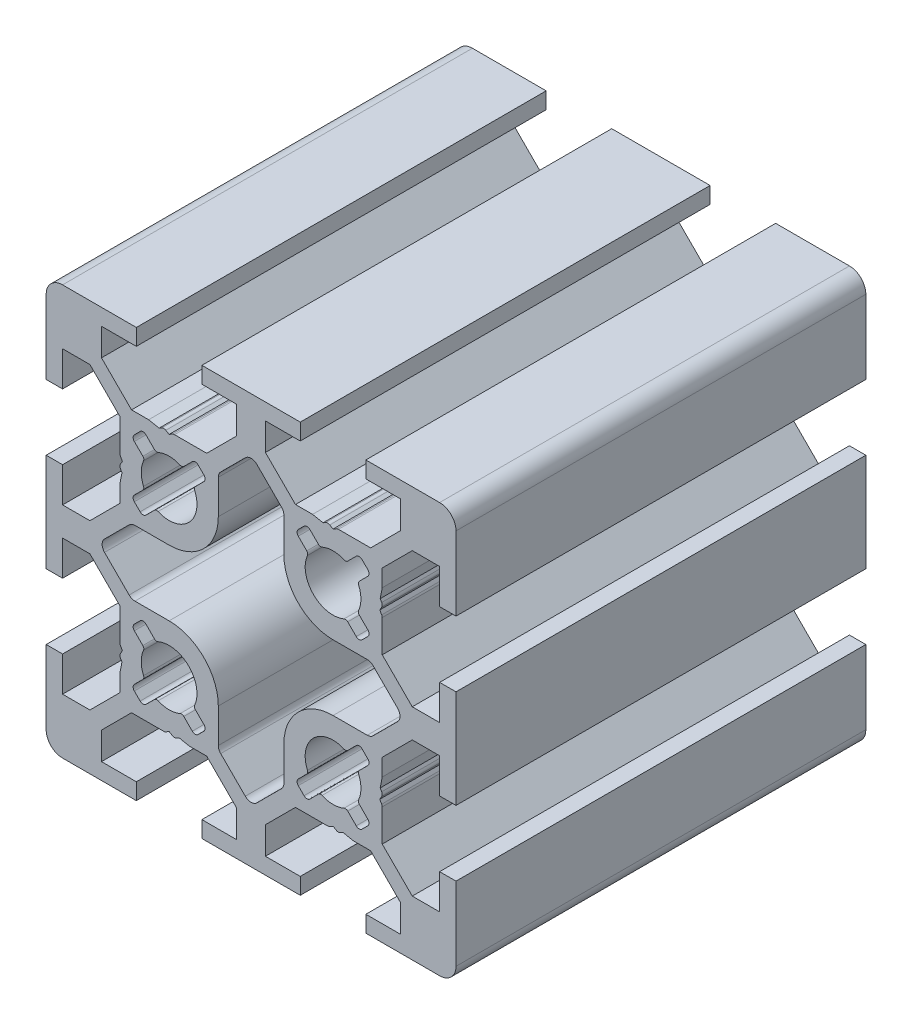
SolidWorks part; units mm, degrees
ref_plane "Front Plane" through (0, 0, 0) normal (0, 0, 1) x (1, 0, 0)
ref_plane "Top Plane" through (0, 0, 0) normal (0, 1, 0) x (1, 0, 0)
ref_plane "Right Plane" through (0, 0, 0) normal (1, 0, 0) x (0, 0, -1)
ref_plane "Plane1" through (0, 0, 0) normal (0, 0, 1) x (1, 0, 0)
sketch "Sketch1" plane through (0, 0, 0) normal (0, 0, 1) x (1, 0, 0)
  line L0 (-25, 23) -> (-25, 14)
  line L1 (-25, 14) -> (-23, 14)
  line L2 (-23, 14) -> (-23, 18.25)
  line L3 (-23, 18.25) -> (-19.6642, 18.25)
  line L4 (-19.6642, 18.25) -> (-16, 14.5858)
  line L5 (-16, 14.5858) -> (-16, 10.6536)
  line L6 (-15.933, 10.4036) -> (-15.7, 10)
  line L7 (-15.7, 10) -> (-15.933, 9.5964)
  line L8 (-15.933, 9.0964) -> (-15.751, 8.7811)
  line L9 (-15.751, 8.7811) -> (-16, 7.5)
  line L10 (-16, 7.5) -> (-16, 5.4142)
  line L11 (-16, 5.4142) -> (-19.6642, 1.75)
  line L12 (-19.6642, 1.75) -> (-23, 1.75)
  line L13 (-23, 1.75) -> (-23, 6)
  line L14 (-23, 6) -> (-25, 6)
  line L15 (-25, 6) -> (-25, -6)
  line L16 (-25, -6) -> (-23, -6)
  line L17 (-23, -6) -> (-23, -1.75)
  line L18 (-23, -1.75) -> (-19.6642, -1.75)
  line L19 (-19.6642, -1.75) -> (-16, -5.4142)
  line L20 (-16, -5.4142) -> (-16, -9.3464)
  line L21 (-15.933, -9.5964) -> (-15.7, -10)
  line L22 (-15.7, -10) -> (-15.933, -10.4036)
  line L23 (-15.933, -10.9036) -> (-15.751, -11.2189)
  line L24 (-15.751, -11.2189) -> (-16, -12.5)
  line L25 (-16, -12.5) -> (-16, -14.5858)
  line L26 (-16, -14.5858) -> (-19.6642, -18.25)
  line L27 (-19.6642, -18.25) -> (-23, -18.25)
  line L28 (-23, -18.25) -> (-23, -14)
  line L29 (-23, -14) -> (-25, -14)
  line L30 (-25, -14) -> (-25, -23)
  line L31 (-23, -25) -> (-14, -25)
  line L32 (-14, -25) -> (-14, -23)
  line L33 (-14, -23) -> (-18.25, -23)
  line L34 (-18.25, -23) -> (-18.25, -19.6642)
  line L35 (-18.25, -19.6642) -> (-14.5858, -16)
  line L36 (-14.5858, -16) -> (-10.6536, -16)
  line L37 (-10.4036, -15.933) -> (-10, -15.7)
  line L38 (-10, -15.7) -> (-9.5964, -15.933)
  line L39 (-9.0964, -15.933) -> (-8.7811, -15.751)
  line L40 (-8.7811, -15.751) -> (-7.5, -16)
  line L41 (-7.5, -16) -> (-5.4142, -16)
  line L42 (-5.4142, -16) -> (-1.75, -19.6642)
  line L43 (-1.75, -19.6642) -> (-1.75, -23)
  line L44 (-1.75, -23) -> (-6, -23)
  line L45 (-6, -23) -> (-6, -25)
  line L46 (-6, -25) -> (6, -25)
  line L47 (6, -25) -> (6, -23)
  line L48 (6, -23) -> (1.75, -23)
  line L49 (1.75, -23) -> (1.75, -19.6642)
  line L50 (1.75, -19.6642) -> (5.4142, -16)
  line L51 (5.4142, -16) -> (9.3464, -16)
  line L52 (9.5964, -15.933) -> (10, -15.7)
  line L53 (10, -15.7) -> (10.4036, -15.933)
  line L54 (10.9036, -15.933) -> (11.2189, -15.751)
  line L55 (11.2189, -15.751) -> (12.5, -16)
  line L56 (12.5, -16) -> (14.5858, -16)
  line L57 (14.5858, -16) -> (18.25, -19.6642)
  line L58 (18.25, -19.6642) -> (18.25, -23)
  line L59 (18.25, -23) -> (14, -23)
  line L60 (14, -23) -> (14, -25)
  line L61 (14, -25) -> (23, -25)
  line L62 (25, -23) -> (25, -14)
  line L63 (25, -14) -> (23, -14)
  line L64 (23, -14) -> (23, -18.25)
  line L65 (23, -18.25) -> (19.6642, -18.25)
  line L66 (19.6642, -18.25) -> (16, -14.5858)
  line L67 (16, -14.5858) -> (16, -10.6536)
  line L68 (15.933, -10.4036) -> (15.7, -10)
  line L69 (15.7, -10) -> (15.933, -9.5964)
  line L70 (15.933, -9.0964) -> (15.751, -8.7811)
  line L71 (15.751, -8.7811) -> (16, -7.5)
  line L72 (16, -7.5) -> (16, -5.4142)
  line L73 (16, -5.4142) -> (19.6642, -1.75)
  line L74 (19.6642, -1.75) -> (23, -1.75)
  line L75 (23, -1.75) -> (23, -6)
  line L76 (23, -6) -> (25, -6)
  line L77 (25, -6) -> (25, 6)
  line L78 (25, 6) -> (23, 6)
  line L79 (23, 6) -> (23, 1.75)
  line L80 (23, 1.75) -> (19.6642, 1.75)
  line L81 (19.6642, 1.75) -> (16, 5.4142)
  line L82 (16, 5.4142) -> (16, 9.3464)
  line L83 (15.933, 9.5964) -> (15.7, 10)
  line L84 (15.7, 10) -> (15.933, 10.4036)
  line L85 (15.933, 10.9036) -> (15.751, 11.2189)
  line L86 (15.751, 11.2189) -> (16, 12.5)
  line L87 (16, 12.5) -> (16, 14.5858)
  line L88 (16, 14.5858) -> (19.6642, 18.25)
  line L89 (19.6642, 18.25) -> (23, 18.25)
  line L90 (23, 18.25) -> (23, 14)
  line L91 (23, 14) -> (25, 14)
  line L92 (25, 14) -> (25, 23)
  line L93 (23, 25) -> (14, 25)
  line L94 (14, 25) -> (14, 23)
  line L95 (14, 23) -> (18.25, 23)
  line L96 (18.25, 23) -> (18.25, 19.6642)
  line L97 (18.25, 19.6642) -> (14.5858, 16)
  line L98 (14.5858, 16) -> (10.6536, 16)
  line L99 (10.4036, 15.933) -> (10, 15.7)
  line L100 (10, 15.7) -> (9.5964, 15.933)
  line L101 (9.0964, 15.933) -> (8.7811, 15.751)
  line L102 (8.7811, 15.751) -> (7.5, 16)
  line L103 (7.5, 16) -> (5.4142, 16)
  line L104 (5.4142, 16) -> (1.75, 19.6642)
  line L105 (1.75, 19.6642) -> (1.75, 23)
  line L106 (1.75, 23) -> (6, 23)
  line L107 (6, 23) -> (6, 25)
  line L108 (6, 25) -> (-6, 25)
  line L109 (-6, 25) -> (-6, 23)
  line L110 (-6, 23) -> (-1.75, 23)
  line L111 (-1.75, 23) -> (-1.75, 19.6642)
  line L112 (-1.75, 19.6642) -> (-5.4142, 16)
  line L113 (-5.4142, 16) -> (-9.3464, 16)
  line L114 (-9.5964, 15.933) -> (-10, 15.7)
  line L115 (-10, 15.7) -> (-10.4036, 15.933)
  line L116 (-10.9036, 15.933) -> (-11.2189, 15.751)
  line L117 (-11.2189, 15.751) -> (-12.5, 16)
  line L118 (-12.5, 16) -> (-14.5858, 16)
  line L119 (-14.5858, 16) -> (-18.25, 19.6642)
  line L120 (-18.25, 19.6642) -> (-18.25, 23)
  line L121 (-18.25, 23) -> (-14, 23)
  line L122 (-14, 23) -> (-14, 25)
  line L123 (-14, 25) -> (-23, 25)
  line L124 (-17.8787, -0.7071) -> (-14.8787, -3.7071)
  line L125 (-14.1716, -4) -> (-10, -4)
  line L126 (-4, -10) -> (-4, -14.1716)
  line L127 (-3.7071, -14.8787) -> (-0.7071, -17.8787)
  line L128 (0.7071, -17.8787) -> (3.7071, -14.8787)
  line L129 (4, -14.1716) -> (4, -10)
  line L130 (10, -4) -> (14.1716, -4)
  line L131 (14.8787, -3.7071) -> (17.8787, -0.7071)
  line L132 (17.8787, 0.7071) -> (14.8787, 3.7071)
  line L133 (14.1716, 4) -> (10, 4)
  line L134 (4, 10) -> (4, 14.1716)
  line L135 (3.7071, 14.8787) -> (0.7071, 17.8787)
  line L136 (-0.7071, 17.8787) -> (-3.7071, 14.8787)
  line L137 (-4, 14.1716) -> (-4, 10)
  line L138 (-10, 4) -> (-14.1716, 4)
  line L139 (-14.8787, 3.7071) -> (-17.8787, 0.7071)
  arc A0 (-16, 10.6536) -> (-15.933, 10.4036) centre (-15.5, 10.6536) ccw
  arc A1 (-15.933, 9.5964) -> (-15.933, 9.0964) centre (-15.5, 9.3464) ccw
  arc A2 (-16, -9.3464) -> (-15.933, -9.5964) centre (-15.5, -9.3464) ccw
  arc A3 (-15.933, -10.4036) -> (-15.933, -10.9036) centre (-15.5, -10.6536) ccw
  arc A4 (-25, -23) -> (-23, -25) centre (-23, -23) ccw
  arc A5 (-10.6536, -16) -> (-10.4036, -15.933) centre (-10.6536, -15.5) ccw
  arc A6 (-9.5964, -15.933) -> (-9.0964, -15.933) centre (-9.3464, -15.5) ccw
  arc A7 (9.3464, -16) -> (9.5964, -15.933) centre (9.3464, -15.5) ccw
  arc A8 (10.4036, -15.933) -> (10.9036, -15.933) centre (10.6536, -15.5) ccw
  arc A9 (23, -25) -> (25, -23) centre (23, -23) ccw
  arc A10 (16, -10.6536) -> (15.933, -10.4036) centre (15.5, -10.6536) ccw
  arc A11 (15.933, -9.5964) -> (15.933, -9.0964) centre (15.5, -9.3464) ccw
  arc A12 (16, 9.3464) -> (15.933, 9.5964) centre (15.5, 9.3464) ccw
  arc A13 (15.933, 10.4036) -> (15.933, 10.9036) centre (15.5, 10.6536) ccw
  arc A14 (25, 23) -> (23, 25) centre (23, 23) ccw
  arc A15 (10.6536, 16) -> (10.4036, 15.933) centre (10.6536, 15.5) ccw
  arc A16 (9.5964, 15.933) -> (9.0964, 15.933) centre (9.3464, 15.5) ccw
  arc A17 (-9.3464, 16) -> (-9.5964, 15.933) centre (-9.3464, 15.5) ccw
  arc A18 (-10.4036, 15.933) -> (-10.9036, 15.933) centre (-10.6536, 15.5) ccw
  arc A19 (-23, 25) -> (-25, 23) centre (-23, 23) ccw
  arc A20 (-17.8787, 0.7071) -> (-17.8787, -0.7071) centre (-17.1716, 0) ccw
  arc A21 (-14.8787, -3.7071) -> (-14.1716, -4) centre (-14.1716, -3) ccw
  arc A22 (-10, -4) -> (-4, -10) centre (-10, -10) cw
  arc A23 (-4, -14.1716) -> (-3.7071, -14.8787) centre (-3, -14.1716) ccw
  arc A24 (-0.7071, -17.8787) -> (0.7071, -17.8787) centre (0, -17.1716) ccw
  arc A25 (3.7071, -14.8787) -> (4, -14.1716) centre (3, -14.1716) ccw
  arc A26 (4, -10) -> (10, -4) centre (10, -10) cw
  arc A27 (14.1716, -4) -> (14.8787, -3.7071) centre (14.1716, -3) ccw
  arc A28 (17.8787, -0.7071) -> (17.8787, 0.7071) centre (17.1716, 0) ccw
  arc A29 (14.8787, 3.7071) -> (14.1716, 4) centre (14.1716, 3) ccw
  arc A30 (10, 4) -> (4, 10) centre (10, 10) cw
  arc A31 (4, 14.1716) -> (3.7071, 14.8787) centre (3, 14.1716) ccw
  arc A32 (0.7071, 17.8787) -> (-0.7071, 17.8787) centre (0, 17.1716) ccw
  arc A33 (-3.7071, 14.8787) -> (-4, 14.1716) centre (-3, 14.1716) ccw
  arc A34 (-4, 10) -> (-10, 4) centre (-10, 10) cw
  arc A35 (-14.1716, 4) -> (-14.8787, 3.7071) centre (-14.1716, 3) ccw
extrude "Boss-Extrude1" add sketch "Sketch1" against normal blind 50
ref_plane "Plane2" through (0, 0, 0) normal (0, 0, 1) x (1, 0, 0)
sketch "Sketch2" plane through (0, 0, 0) normal (0, 0, 1) x (1, 0, 0)
  line L0 (-14.2426, 12.8284) -> (-13.2051, 11.7909)
  line L1 (-13.2051, 8.2091) -> (-14.2426, 7.1716)
  line L2 (-14.2426, 6.4645) -> (-13.5355, 5.7574)
  line L3 (-12.8284, 5.7574) -> (-11.7909, 6.7949)
  line L4 (-6.7949, 11.7909) -> (-5.7574, 12.8284)
  line L5 (-5.7574, 13.5355) -> (-6.4645, 14.2426)
  line L6 (-7.1716, 14.2426) -> (-8.2091, 13.2051)
  line L7 (-11.7909, 13.2051) -> (-12.8284, 14.2426)
  line L8 (-13.5355, 14.2426) -> (-14.2426, 13.5355)
  arc A0 (-14.2426, 13.5355) -> (-14.2426, 12.8284) centre (-13.8891, 13.182) ccw
  arc A1 (-13.2051, 11.7909) -> (-13.1208, 11.3493) centre (-13.4879, 11.508) cw
  arc A2 (-13.1208, 11.3493) -> (-13.1208, 8.6507) centre (-10, 10) ccw
  arc A3 (-13.1208, 8.6507) -> (-13.2051, 8.2091) centre (-13.4879, 8.492) cw
  arc A4 (-14.2426, 7.1716) -> (-14.2426, 6.4645) centre (-13.8891, 6.818) ccw
  arc A5 (-13.5355, 5.7574) -> (-12.8284, 5.7574) centre (-13.182, 6.1109) ccw
  arc A6 (-11.7909, 6.7949) -> (-11.3493, 6.8792) centre (-11.508, 6.5121) cw
  arc A7 (-11.3493, 6.8792) -> (-6.8792, 11.3493) centre (-10, 10) ccw
  arc A8 (-6.8792, 11.3493) -> (-6.7949, 11.7909) centre (-6.5121, 11.508) cw
  arc A9 (-5.7574, 12.8284) -> (-5.7574, 13.5355) centre (-6.1109, 13.182) ccw
  arc A10 (-6.4645, 14.2426) -> (-7.1716, 14.2426) centre (-6.818, 13.8891) ccw
  arc A11 (-8.2091, 13.2051) -> (-8.6507, 13.1208) centre (-8.492, 13.4879) cw
  arc A12 (-8.6507, 13.1208) -> (-11.3493, 13.1208) centre (-10, 10) ccw
  arc A13 (-11.3493, 13.1208) -> (-11.7909, 13.2051) centre (-11.508, 13.4879) cw
  arc A14 (-12.8284, 14.2426) -> (-13.5355, 14.2426) centre (-13.182, 13.8891) ccw
extrude "Cut-Extrude1" cut sketch "Sketch2" against normal blind 50
ref_plane "Plane3" through (0, 0, 0) normal (0, 0, 1) x (1, 0, 0)
sketch "Sketch3" plane through (0, 0, 0) normal (0, 0, 1) x (1, 0, 0)
  line L0 (-12.8284, -14.2426) -> (-11.7909, -13.2051)
  line L1 (-8.2091, -13.2051) -> (-7.1716, -14.2426)
  line L2 (-6.4645, -14.2426) -> (-5.7574, -13.5355)
  line L3 (-5.7574, -12.8284) -> (-6.7949, -11.7909)
  line L4 (-11.7909, -6.7949) -> (-12.8284, -5.7574)
  line L5 (-13.5355, -5.7574) -> (-14.2426, -6.4645)
  line L6 (-14.2426, -7.1716) -> (-13.2051, -8.2091)
  line L7 (-13.2051, -11.7909) -> (-14.2426, -12.8284)
  line L8 (-14.2426, -13.5355) -> (-13.5355, -14.2426)
  arc A0 (-13.5355, -14.2426) -> (-12.8284, -14.2426) centre (-13.182, -13.8891) ccw
  arc A1 (-11.7909, -13.2051) -> (-11.3493, -13.1208) centre (-11.508, -13.4879) cw
  arc A2 (-11.3493, -13.1208) -> (-8.6507, -13.1208) centre (-10, -10) ccw
  arc A3 (-8.6507, -13.1208) -> (-8.2091, -13.2051) centre (-8.492, -13.4879) cw
  arc A4 (-7.1716, -14.2426) -> (-6.4645, -14.2426) centre (-6.818, -13.8891) ccw
  arc A5 (-5.7574, -13.5355) -> (-5.7574, -12.8284) centre (-6.1109, -13.182) ccw
  arc A6 (-6.7949, -11.7909) -> (-6.8792, -11.3493) centre (-6.5121, -11.508) cw
  arc A7 (-6.8792, -11.3493) -> (-11.3493, -6.8792) centre (-10, -10) ccw
  arc A8 (-11.3493, -6.8792) -> (-11.7909, -6.7949) centre (-11.508, -6.5121) cw
  arc A9 (-12.8284, -5.7574) -> (-13.5355, -5.7574) centre (-13.182, -6.1109) ccw
  arc A10 (-14.2426, -6.4645) -> (-14.2426, -7.1716) centre (-13.8891, -6.818) ccw
  arc A11 (-13.2051, -8.2091) -> (-13.1208, -8.6507) centre (-13.4879, -8.492) cw
  arc A12 (-13.1208, -8.6507) -> (-13.1208, -11.3493) centre (-10, -10) ccw
  arc A13 (-13.1208, -11.3493) -> (-13.2051, -11.7909) centre (-13.4879, -11.508) cw
  arc A14 (-14.2426, -12.8284) -> (-14.2426, -13.5355) centre (-13.8891, -13.182) ccw
extrude "Cut-Extrude2" cut sketch "Sketch3" against normal blind 50
ref_plane "Plane4" through (0, 0, 0) normal (0, 0, 1) x (1, 0, 0)
sketch "Sketch4" plane through (0, 0, 0) normal (0, 0, 1) x (1, 0, 0)
  line L0 (14.2426, -12.8284) -> (13.2051, -11.7909)
  line L1 (13.2051, -8.2091) -> (14.2426, -7.1716)
  line L2 (14.2426, -6.4645) -> (13.5355, -5.7574)
  line L3 (12.8284, -5.7574) -> (11.7909, -6.7949)
  line L4 (6.7949, -11.7909) -> (5.7574, -12.8284)
  line L5 (5.7574, -13.5355) -> (6.4645, -14.2426)
  line L6 (7.1716, -14.2426) -> (8.2091, -13.2051)
  line L7 (11.7909, -13.2051) -> (12.8284, -14.2426)
  line L8 (13.5355, -14.2426) -> (14.2426, -13.5355)
  arc A0 (14.2426, -13.5355) -> (14.2426, -12.8284) centre (13.8891, -13.182) ccw
  arc A1 (13.2051, -11.7909) -> (13.1208, -11.3493) centre (13.4879, -11.508) cw
  arc A2 (13.1208, -11.3493) -> (13.1208, -8.6507) centre (10, -10) ccw
  arc A3 (13.1208, -8.6507) -> (13.2051, -8.2091) centre (13.4879, -8.492) cw
  arc A4 (14.2426, -7.1716) -> (14.2426, -6.4645) centre (13.8891, -6.818) ccw
  arc A5 (13.5355, -5.7574) -> (12.8284, -5.7574) centre (13.182, -6.1109) ccw
  arc A6 (11.7909, -6.7949) -> (11.3493, -6.8792) centre (11.508, -6.5121) cw
  arc A7 (11.3493, -6.8792) -> (6.8792, -11.3493) centre (10, -10) ccw
  arc A8 (6.8792, -11.3493) -> (6.7949, -11.7909) centre (6.5121, -11.508) cw
  arc A9 (5.7574, -12.8284) -> (5.7574, -13.5355) centre (6.1109, -13.182) ccw
  arc A10 (6.4645, -14.2426) -> (7.1716, -14.2426) centre (6.818, -13.8891) ccw
  arc A11 (8.2091, -13.2051) -> (8.6507, -13.1208) centre (8.492, -13.4879) cw
  arc A12 (8.6507, -13.1208) -> (11.3493, -13.1208) centre (10, -10) ccw
  arc A13 (11.3493, -13.1208) -> (11.7909, -13.2051) centre (11.508, -13.4879) cw
  arc A14 (12.8284, -14.2426) -> (13.5355, -14.2426) centre (13.182, -13.8891) ccw
extrude "Cut-Extrude3" cut sketch "Sketch4" against normal blind 50
ref_plane "Plane5" through (0, 0, 0) normal (0, 0, 1) x (1, 0, 0)
sketch "Sketch5" plane through (0, 0, 0) normal (0, 0, 1) x (1, 0, 0)
  line L0 (12.8284, 14.2426) -> (11.7909, 13.2051)
  line L1 (8.2091, 13.2051) -> (7.1716, 14.2426)
  line L2 (6.4645, 14.2426) -> (5.7574, 13.5355)
  line L3 (5.7574, 12.8284) -> (6.7949, 11.7909)
  line L4 (11.7909, 6.7949) -> (12.8284, 5.7574)
  line L5 (13.5355, 5.7574) -> (14.2426, 6.4645)
  line L6 (14.2426, 7.1716) -> (13.2051, 8.2091)
  line L7 (13.2051, 11.7909) -> (14.2426, 12.8284)
  line L8 (14.2426, 13.5355) -> (13.5355, 14.2426)
  arc A0 (13.5355, 14.2426) -> (12.8284, 14.2426) centre (13.182, 13.8891) ccw
  arc A1 (11.7909, 13.2051) -> (11.3493, 13.1208) centre (11.508, 13.4879) cw
  arc A2 (11.3493, 13.1208) -> (8.6507, 13.1208) centre (10, 10) ccw
  arc A3 (8.6507, 13.1208) -> (8.2091, 13.2051) centre (8.492, 13.4879) cw
  arc A4 (7.1716, 14.2426) -> (6.4645, 14.2426) centre (6.818, 13.8891) ccw
  arc A5 (5.7574, 13.5355) -> (5.7574, 12.8284) centre (6.1109, 13.182) ccw
  arc A6 (6.7949, 11.7909) -> (6.8792, 11.3493) centre (6.5121, 11.508) cw
  arc A7 (6.8792, 11.3493) -> (11.3493, 6.8792) centre (10, 10) ccw
  arc A8 (11.3493, 6.8792) -> (11.7909, 6.7949) centre (11.508, 6.5121) cw
  arc A9 (12.8284, 5.7574) -> (13.5355, 5.7574) centre (13.182, 6.1109) ccw
  arc A10 (14.2426, 6.4645) -> (14.2426, 7.1716) centre (13.8891, 6.818) ccw
  arc A11 (13.2051, 8.2091) -> (13.1208, 8.6507) centre (13.4879, 8.492) cw
  arc A12 (13.1208, 8.6507) -> (13.1208, 11.3493) centre (10, 10) ccw
  arc A13 (13.1208, 11.3493) -> (13.2051, 11.7909) centre (13.4879, 11.508) cw
  arc A14 (14.2426, 12.8284) -> (14.2426, 13.5355) centre (13.8891, 13.182) ccw
extrude "Cut-Extrude4" cut sketch "Sketch5" against normal blind 50
